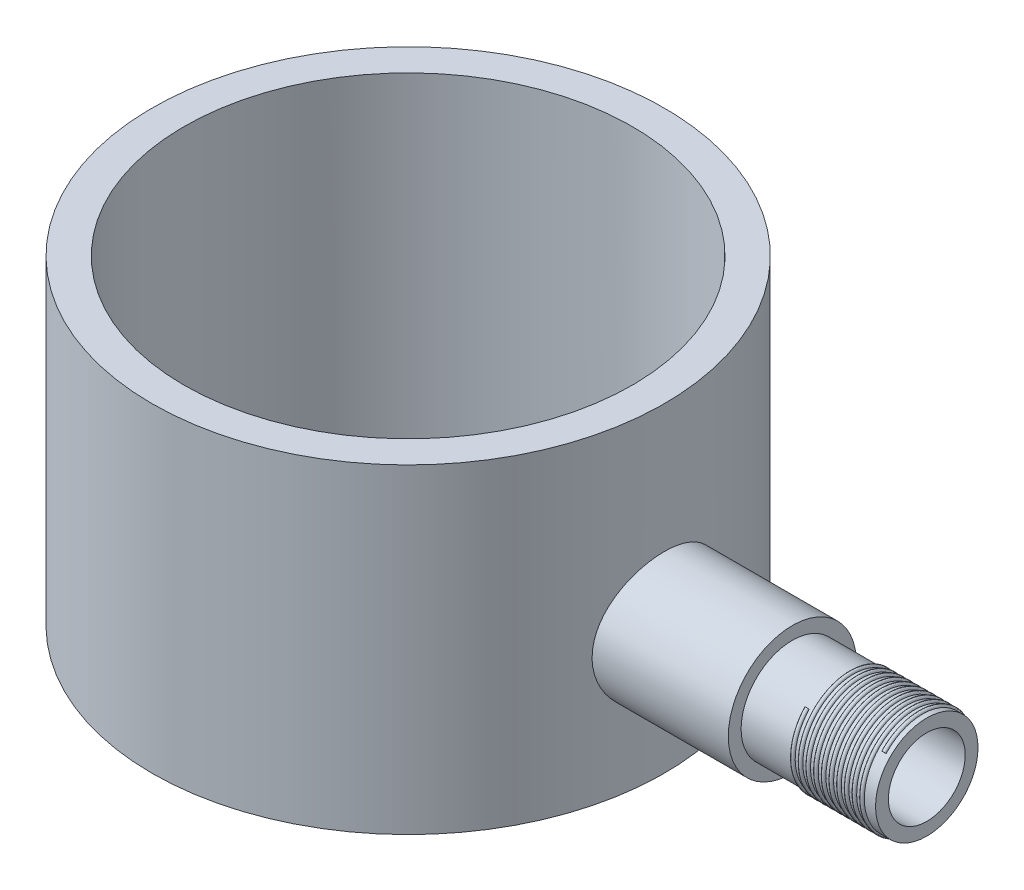
SolidWorks part; units mm, degrees
ref_plane "Front Plane" through (0, 0, 0) normal (0, 0, 1) x (1, 0, 0)
ref_plane "Top Plane" through (0, 0, 0) normal (0, 1, 0) x (1, 0, 0)
ref_plane "Right Plane" through (0, 0, 0) normal (1, 0, 0) x (0, 0, -1)
sketch "Sketch2" plane through (0, 0, 0) normal (0, 1, 0) x (1, 0, 0)
  circle A0 centre (0, 0) radius 35
  circle A1 centre (0, 0) radius 40
extrude "Boss-Extrude1" add sketch "Sketch2" along normal blind 50
sketch "Sketch3" plane through (0, 0, 0) normal (0, -1, 0) x (-1, 0, 0)
  line L0 (0, 0) -> (0, -35)
  line L1 (0, -35) -> (-2, -35)
  line L2 (-2, -35) -> (-2, 0)
  line L3 (-2, 0) -> (-35, 0)
  line L4 (-35, 0) -> (-35, 2)
  line L5 (-35, 2) -> (-2, 2)
  line L6 (-2, 2) -> (-2, 35)
  line L7 (-2, 35) -> (2, 35)
  line L8 (2, 35) -> (2, 2)
  line L9 (2, 2) -> (34.9938, 2)
  line L10 (34.9938, 2) -> (34.9938, -2)
  line L11 (34.9938, -2) -> (1.9938, -2)
  line L12 (1.9938, -2) -> (1.9938, -35)
  line L13 (1.9938, -35) -> (0, -35)
  line L14 (-35, 0) -> (-35, -2)
  line L15 (-35, -2) -> (-2, -2)
  circle A0 centre (0, 0) radius 35 construction
  circle A1 centre (0, 0) radius 21
extrude "Boss-Extrude2" add sketch "Sketch3" against normal blind 6
sketch "Sketch4" plane through (0, 0, 0) normal (0, -1, 0) x (-1, 0, 0)
  circle A0 centre (0, 0) radius 8
  circle A1 centre (0, 0) radius 9.5
  circle A2 centre (-8, 0) radius 1.5
  circle A3 centre (8, 0) radius 1.5
  circle A4 centre (0, -9.5) radius 1.5
  circle A5 centre (0, 9.5) radius 1.5
  circle A6 centre (0, 0) radius 16.25
  circle A7 centre (0, -16.25) radius 1.5
  circle A8 centre (-16.25, 0) radius 1.5
  circle A9 centre (0, 16.25) radius 1.5
  circle A10 centre (16.25, 0) radius 1.5
extrude "Cut-Extrude2" cut sketch "Sketch4" against normal blind 6 contours A10 | A7 | A8 | A9 | A5 | A2 | A4 | A3
sketch "Sketch5" plane through (0, 0, 0) normal (0, 0, 1) x (1, 0, 0)
  line L0 (0, 0) -> (0, 20) construction
  line L1 (0, 20) -> (80, 20) construction
  line L3 (80, 14) -> (38, 14)
  line L4 (38, 14) -> (38, 10)
  line L5 (38, 10) -> (60, 10)
  line L6 (60, 10) -> (60, 12)
  line L7 (60, 12) -> (80, 12)
  line L8 (80, 12) -> (80, 14)
revolve "Revolve4" add sketch "Sketch5" angle 360 about L1
sketch "Sketch12" plane through (80, 0, 0) normal (1, 0, 0) x (0, 0, -1)
  circle A0 centre (0, 20) radius 6
extrude "Cut-Extrude6" cut sketch "Sketch12" against normal blind 60
sketch "Sketch13" plane through (80, 0, 0) normal (1, 0, 0) x (0, 0, -1)
  circle A0 centre (0, 20) radius 8
curve "Helix/Spiral1" pitch 1.2 height 12 turns 10
sweep "Sweep1" add path "Helix/Spiral1" circular profile diameter 0.6 parameters "D3"=0.6
sketch "Sketch30" plane through (80, 0, 0) normal (1, 0, 0) x (0, 0, -1)
  circle A0 centre (0, 20) radius 8
extrude "Boss-Extrude3" add sketch "Sketch30" along normal blind 1
sketch "Sketch31" plane through (81, 0, 0) normal (1, 0, 0) x (0, 0, -1)
  circle A0 centre (0, 20) radius 6
extrude "Cut-Extrude7" cut sketch "Sketch31" against normal blind 1
